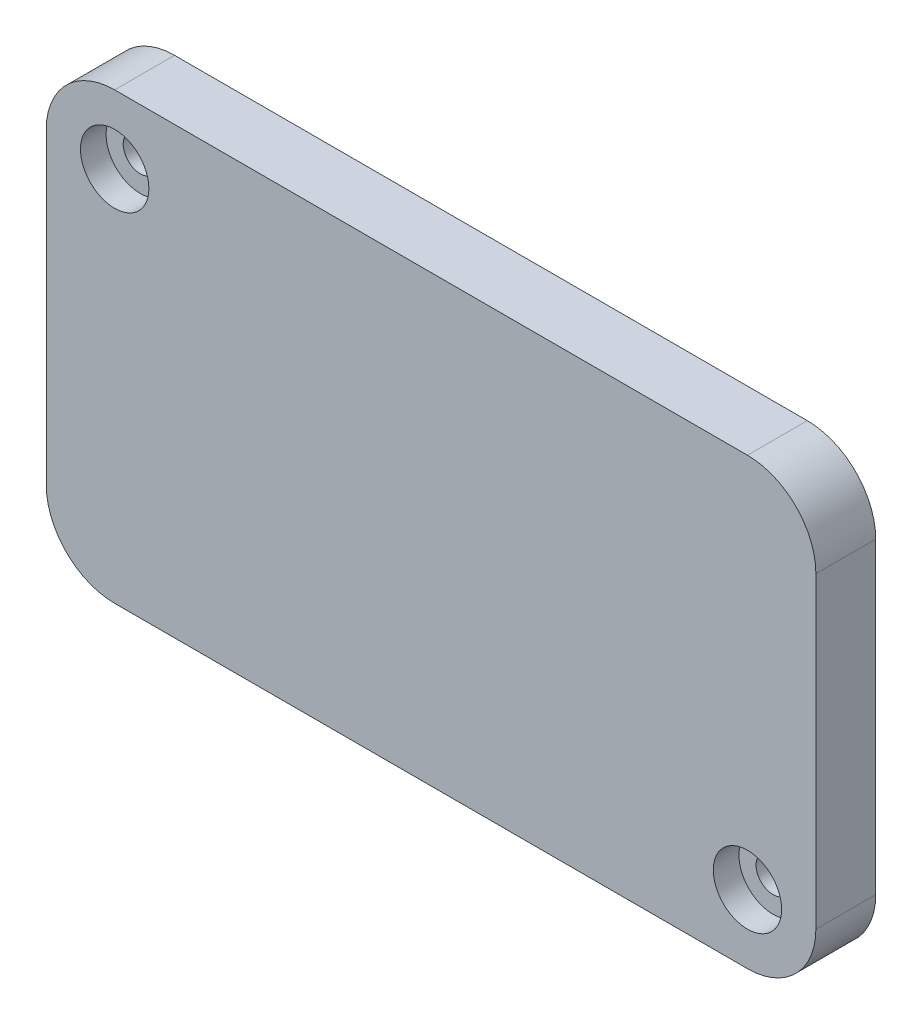
SolidWorks part; units mm, degrees
ref_plane "Front Plane" through (0, 0, 0) normal (0, 0, 1) x (1, 0, 0)
ref_plane "Top Plane" through (0, 0, 0) normal (0, 1, 0) x (1, 0, 0)
ref_plane "Right Plane" through (0, 0, 0) normal (1, 0, 0) x (0, 0, -1)
sketch "Sketch1" plane through (0, 0, 0) normal (0, 0, 1) x (1, 0, 0)
  line L1 (-4, 4) -> (41, 4)
  line L2 (-4, 4) -> (-4, -22)
  line L3 (-4, -22) -> (41, -22)
  line L4 (41, 4) -> (41, -22)
  circle A0 centre (0, 0) radius 1
  circle A1 centre (37, -18) radius 1
  point P4 (41.978, -22.7564)
  dimension "D2" = 2
  dimension "D1" = 18
  dimension "D3" = 37
  dimension "D4" = 4
  dimension "D5" = 4
  dimension "D6" = 4
  dimension "D7" = 4
extrude "Boss-Extrude1" add sketch "Sketch1" along normal blind 3.5
fillet "Fillet1" radius 4 4 edges at (-4, 4, 1.75) (-4, -22, 1.75) (41, -22, 1.75) (41, 4, 1.75)
sketch "Sketch2" plane through (0, 0, 3.5) normal (0, 0, 1) x (1, 0, 0)
  circle A0 centre (37, -18) radius 2
  circle A1 centre (0, 0) radius 2
  dimension "D1" = 4
extrude "Cut-Extrude1" cut sketch "Sketch2" against normal blind 1.5
